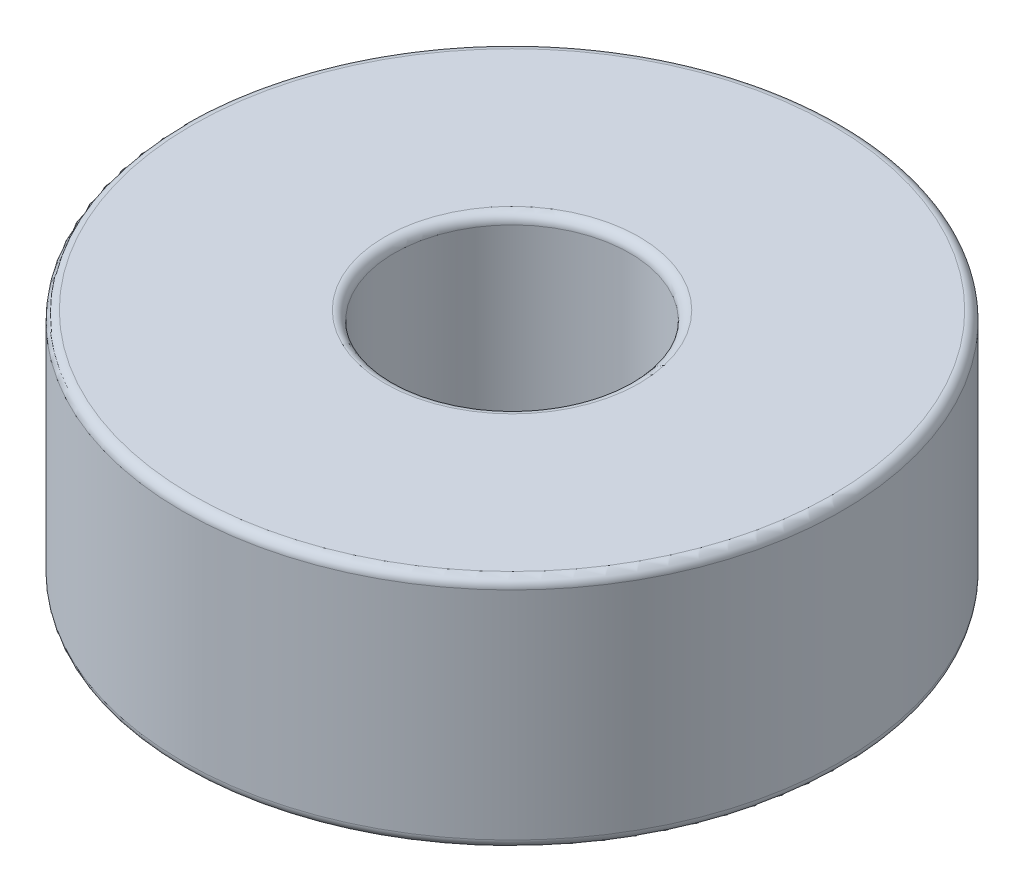
SolidWorks part; units mm, degrees
ref_plane "Front Plane" through (0, 0, 0) normal (0, 0, 1) x (1, 0, 0)
ref_plane "Top Plane" through (0, 0, 0) normal (0, 1, 0) x (1, 0, 0)
ref_plane "Right Plane" through (0, 0, 0) normal (1, 0, 0) x (0, 0, -1)
sketch "Sketch1" plane through (0, 0, 0) normal (0, 1, 0) x (1, 0, 0)
  circle A0 centre (0, 0) radius 2.5
  circle A1 centre (0, 0) radius 7
  dimension "D1" = 5
  dimension "D2" = 14
extrude "Boss-Extrude1" add sketch "Sketch1" along normal mid plane 5
fillet "Fillet1" radius 0.2 4 edges at (0, -2.5, 2.5) (0, -2.5, 7) (0, 2.5, 2.5) (0, 2.5, 7)
